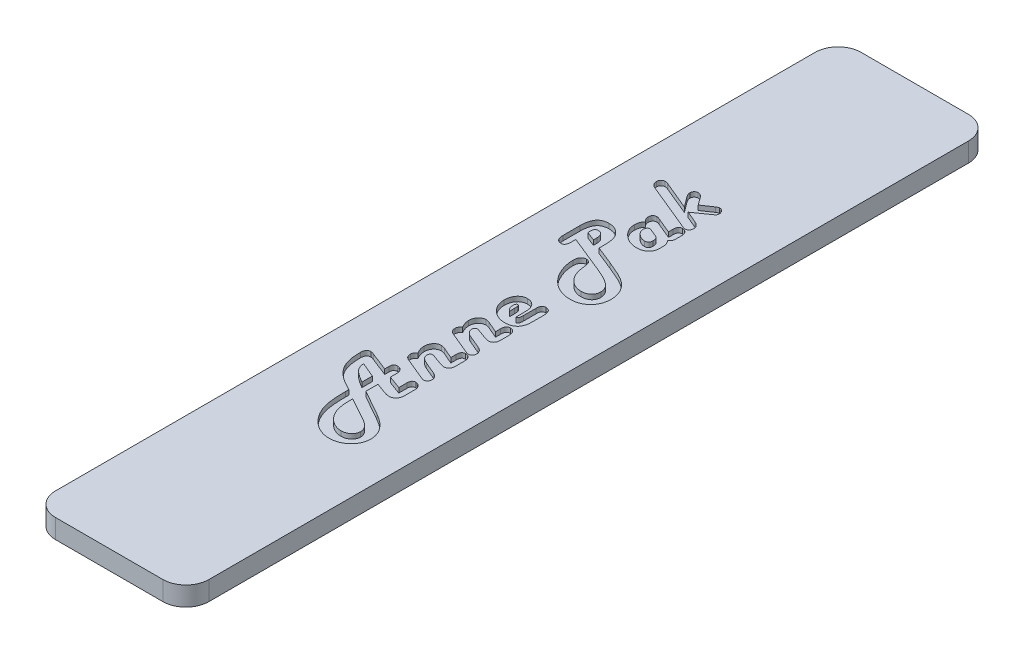
SolidWorks part; units mm, degrees
ref_plane "Front Plane" through (0, 0, 0) normal (0, 0, 1) x (1, 0, 0)
ref_plane "Top Plane" through (0, 0, 0) normal (0, 1, 0) x (1, 0, 0)
ref_plane "Right Plane" through (0, 0, 0) normal (1, 0, 0) x (0, 0, -1)
sketch "Sketch1" plane through (0, 0, 0) normal (0, 0, 1) x (1, 0, 0)
  line L0 (0, 1.5875) -> (0, -1.5875)
  line L1 (-12.7, 0) -> (12.7, 0) construction
  point P6 (0, 0)
  dimension "Width" = 25.4
  dimension "Thk" = 3.175
sketch "Sketch2" plane through (0, 0, 0) normal (1, 0, 0) x (0, 0, -1)
  line L0 (66.675, 0) -> (-66.675, 0)
  point P4 (0, 0)
  dimension "Length" = 133.35
sketch "Sketch3" plane through (0, 0, 0) normal (0, 0, 1) x (1, 0, 0)
  line L1 (12.7, 1.5875) -> (-12.7, 1.5875)
  line L2 (12.7, 1.5875) -> (12.7, -1.5875)
  line L3 (12.7, -1.5875) -> (-12.7, -1.5875)
  line L4 (-12.7, 1.5875) -> (-12.7, -1.5875)
  line L5 (12.7, 1.5875) -> (-12.7, -1.5875) construction
  line L6 (12.7, -1.5875) -> (-12.7, 1.5875) construction
  point P0 (0, 0)
extrude "Boss-Extrude1" add sketch "Sketch3" along normal up to vertex (66.675 mm away) and the other way up to vertex (66.675 mm away) up to point (0, 0, 66.675) other way up to point (0, 0, -66.675)
sketch "Sketch5" plane through (0, 1.5875, 0) normal (0, 1, 0) x (1, 0, 0)
  line L0 (-9.398, 66.929) -> (9.652, 66.929) construction
  line L1 (12.954, 63.627) -> (12.954, -63.373) construction
  line L2 (9.652, -66.675) -> (-9.398, -66.675) construction
  line L3 (-12.7, -63.373) -> (-12.7, 63.627) construction
  line L12 (12.7, -66.675) -> (12.7, 66.675)
  line L13 (12.7, 66.675) -> (-12.7, 66.675)
  line L14 (-12.7, 66.675) -> (-12.7, -66.675)
  line L15 (-12.7, -66.675) -> (12.7, -66.675)
  line L16 (12.7, -62.865) -> (12.7, 62.865)
  line L17 (8.89, 66.675) -> (-8.89, 66.675)
  line L18 (-12.7, 62.865) -> (-12.7, -62.865)
  line L19 (-8.89, -66.675) -> (8.89, -66.675)
  arc A0 (9.652, -66.675) -> (12.954, -63.373) centre (9.652, -63.373) ccw construction
  arc A1 (9.652, -66.675) -> (12.954, -63.373) centre (9.652, -63.373) ccw construction
  arc A2 (-12.7, -63.373) -> (-9.398, -66.675) centre (-9.398, -63.373) ccw construction
  arc A3 (-12.7, -63.373) -> (-9.398, -66.675) centre (-9.398, -63.373) ccw construction
  arc A4 (12.954, 63.627) -> (9.652, 66.929) centre (9.652, 63.627) ccw construction
  arc A5 (12.954, 63.627) -> (9.652, 66.929) centre (9.652, 63.627) ccw construction
  arc A6 (-9.398, 66.929) -> (-12.7, 63.627) centre (-9.398, 63.627) ccw construction
  arc A7 (-9.398, 66.929) -> (-12.7, 63.627) centre (-9.398, 63.627) ccw construction
  arc A8 (12.7, 62.865) -> (8.89, 66.675) centre (8.89, 62.865) ccw
  arc A9 (-8.89, 66.675) -> (-12.7, 62.865) centre (-8.89, 62.865) ccw
  arc A10 (12.7, -62.865) -> (8.89, -66.675) centre (8.89, -62.865) cw
  arc A11 (-8.89, -66.675) -> (-12.7, -62.865) centre (-8.89, -62.865) cw
  dimension "D2" = 3.81
  dimension "D1" = 0
extrude "Cut-Extrude2" cut sketch "Sketch5" against normal through all flip side to cut
sketch "Sketch4" plane through (0, 1.5875, 0) normal (0, 1, 0) x (1, 0, 0)
  line L0 (0, 0) -> (2.54, 0) construction
  line L1 (2.54, -66.675) -> (2.54, 66.675) construction
  line L2 (8.89, 66.675) -> (-8.89, 66.675) construction
  text T0 "Anne Pak" font "Harlow Solid Italic" height 10
  point P8 (2.54, 0)
  dimension "D1" = 2.54
extrude "Cut-Extrude1" cut sketch "Sketch4" against normal blind 0.7937
